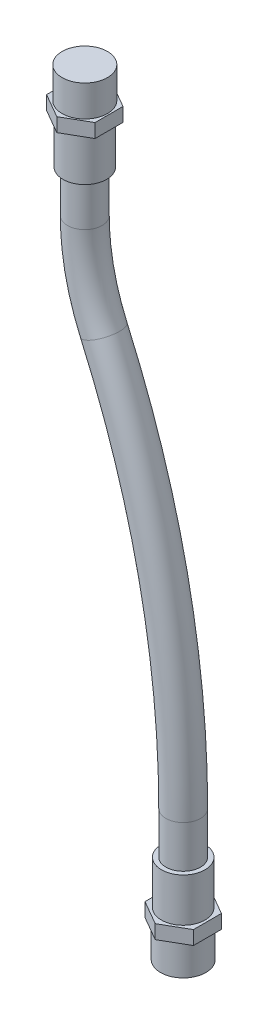
SolidWorks part; units mm, degrees
ref_plane "Front" through (0, 0, 0) normal (0, 0, 1) x (1, 0, 0)
ref_plane "Top" through (0, 0, 0) normal (0, 1, 0) x (1, 0, 0)
ref_plane "Right" through (0, 0, 0) normal (1, 0, 0) x (0, 0, -1)
sketch "Sketch1" plane through (0, 0, 0) normal (0, 0, 1) x (1, 0, 0)
  line L0 (0, 0) -> (0, -30) construction
  line L1 (0, -30) -> (22.5761, -136.5088) construction
  line L2 (22.5761, -136.5088) -> (22.5761, -166.5088) construction
  line L3 (0, -30) -> (0, -7.15)
  line L4 (0, -7.15) -> (0, 0) construction
  line L5 (22.5761, -166.5088) -> (22.5761, -159.3588) construction
  line L6 (22.5761, -159.3588) -> (22.5761, -136.5088)
  arc A0 (22.5761, -136.5088) -> (4.3685, -50.6097) centre (-189.1533, -136.5088) ccw
  arc A2 (4.3685, -50.6097) -> (0, -30) centre (50.8, -30) cw
  point P3 (0, -7.15)
  point P6 (22.5761, -159.3588)
  dimension "D5" = 50.8
  dimension "D6" = 155.3709
  dimension "D1" = 22.5761
  dimension "D2" = 30
  dimension "D3" = 7.15
  dimension "D4" = 152.2088
ref_plane "Plane1" through (0, -7.15, 0) normal (0, 1, 0) x (1, 0, 0)
sketch "Sketch2" plane through (0, -7.15, 0) normal (0, 1, 0) x (1, 0, 0)
  circle A0 centre (0, 0) radius 3.9688
  dimension "D1" = 7.9375
sweep "Sweep1" add profiles "Sketch2" path "Sketch1"
sketch "Sketch3" plane through (0, -7.15, 0) normal (0, 1, 0) x (1, 0, 0)
  line L1 (0, 6.4158) -> (-5.5562, 3.2079)
  line L2 (-5.5562, 3.2079) -> (-5.5562, -3.2079)
  line L3 (-5.5562, -3.2079) -> (0, -6.4158)
  line L4 (0, -6.4158) -> (5.5563, -3.2079)
  line L5 (5.5563, -3.2079) -> (5.5562, 3.2079)
  line L6 (5.5562, 3.2079) -> (0, 6.4158)
  circle A0 centre (0, 0) radius 5.5563 construction
  dimension "D1" = 11.1125
extrude "Boss-Extrude1" add sketch "Sketch3" against normal blind 3.175
sketch "Sketch4" plane through (0, -7.15, 0) normal (0, 1, 0) x (1, 0, 0)
  circle A0 centre (0, 0) radius 5.2022
  dimension "D1" = 10.4043
extrude "Boss-Extrude2" add sketch "Sketch4" along normal up to vertex (7.15 mm away) up to point (0, 0, 0)
sketch "Sketch5" plane through (0, -159.3588, 0) normal (0, -1, 0) x (1, 0, 0)
  line L1 (22.5761, 6.4158) -> (17.0199, 3.2079)
  line L2 (17.0199, 3.2079) -> (17.0199, -3.2079)
  line L3 (17.0199, -3.2079) -> (22.5761, -6.4158)
  line L4 (22.5761, -6.4158) -> (28.1324, -3.2079)
  line L5 (28.1324, -3.2079) -> (28.1324, 3.2079)
  line L6 (28.1324, 3.2079) -> (22.5761, 6.4158)
  circle A0 centre (22.5761, 0) radius 5.5562 construction
  dimension "D1" = 11.1125
extrude "Boss-Extrude3" add sketch "Sketch5" against normal blind 3.175
sketch "Sketch6" plane through (0, -159.3588, 0) normal (0, -1, 0) x (1, 0, 0)
  circle A0 centre (22.5761, 0) radius 5.2022
  circle A1 centre (0, 0) radius 5.2022 construction
extrude "Boss-Extrude4" add sketch "Sketch6" along normal up to vertex (7.15 mm away) up to point (22.5761, -166.5088, 0)
sketch "Sketch7" plane through (0, -10.325, 0) normal (0, -1, 0) x (1, 0, 0)
  circle A0 centre (0, 0) radius 5
  dimension "D1" = 10
extrude "Boss-Extrude5" add sketch "Sketch7" along normal blind 10
sketch "Sketch8" plane through (0, -156.1838, 0) normal (0, 1, 0) x (1, 0, 0)
  circle A0 centre (22.5761, 0) radius 5
  circle A1 centre (0, 0) radius 5 construction
extrude "Boss-Extrude6" add sketch "Sketch8" along normal blind 10
